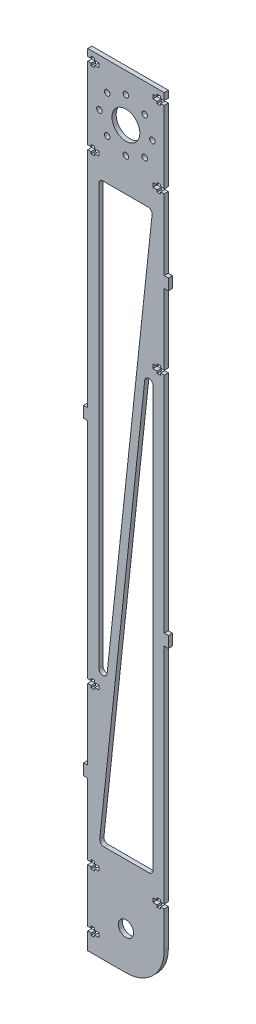
SolidWorks part; units mm, degrees
ref_plane "前视基准面" through (0, 0, 0) normal (0, 0, 1) x (1, 0, 0)
ref_plane "上视基准面" through (0, 0, 0) normal (0, 1, 0) x (1, 0, 0)
ref_plane "右视基准面" through (0, 0, 0) normal (1, 0, 0) x (0, 0, -1)
sketch "草图1" plane through (0, 0, 0) normal (0, 0, 1) x (1, 0, 0)
  line L50 (249.9534, 275.9629) -> (249.9534, 255.9629) construction
  line L71 (269.9534, 275.9629) -> (249.9534, 275.9629) construction
  line L261 (249.9534, 275.9629) -> (249.9534, -224.0371) construction
  line L264 (272.4534, 235.9629) -> (272.4534, -184.0371) construction
  line L265 (272.4534, -184.0371) -> (227.4534, -184.0371) construction
  line L266 (227.4534, -184.0371) -> (227.4534, 235.9629) construction
  line L267 (227.4534, 235.9629) -> (272.4534, 235.9629) construction
  line L268 (272.4534, 235.9629) -> (227.4534, -184.0371) construction
  line L270 (233.4534, 232.9629) -> (265.7762, 232.9629)
  line L271 (268.7591, 229.6433) -> (236.4363, -72.0362)
  line L272 (230.4534, -71.7166) -> (230.4534, 229.9629)
  line L273 (269.4534, 123.6424) -> (269.4534, -178.0371)
  line L274 (266.4534, -181.0371) -> (234.1306, -181.0371)
  line L275 (263.4704, 123.962) -> (231.1476, -177.7175)
  line L276 (269.4534, 179.8027) -> (269.4534, -181.0371) construction
  line L277 (269.4534, -181.0371) -> (230.792, -181.0371) construction
  line L278 (269.4534, 179.8027) -> (230.792, -181.0371) construction
  line L279 (230.4534, -127.8768) -> (230.4534, 232.9629) construction
  line L280 (269.1148, 232.9629) -> (230.4534, -127.8768) construction
  line L281 (230.4534, 232.9629) -> (269.1148, 232.9629) construction
  line L282 (224.9534, -85.2166) -> (224.9534, -86.7166)
  line L283 (224.9534, -82.2166) -> (224.9534, -80.7166)
  line L284 (222.4534, -82.2166) -> (224.9534, -82.2166)
  line L285 (224.9534, -86.7166) -> (227.5534, -86.7166)
  line L286 (227.5534, -86.7166) -> (227.5534, -85.2166)
  line L287 (227.5534, -85.2166) -> (230.5534, -85.2166)
  line L288 (230.5534, -82.2166) -> (230.5534, -85.2166)
  line L289 (227.5534, -82.2166) -> (230.5534, -82.2166)
  line L290 (227.5534, -80.7166) -> (227.5534, -82.2166)
  line L291 (224.9534, -80.7166) -> (227.5534, -80.7166)
  line L292 (224.9534, -85.2166) -> (222.4534, -85.2166)
  line L293 (230.5534, -83.7166) -> (222.4534, -83.7166) construction
  line L294 (233.4534, -71.7166) -> (233.4534, -83.7166) construction
  line L295 (233.4534, -83.7166) -> (222.4534, -83.7166) construction
  line L296 (249.9534, -196.5371) -> (222.4534, -196.5371) construction
  line L297 (249.9534, 248.4629) -> (222.4534, 248.4629) construction
  line L298 (224.9534, -198.0371) -> (224.9534, -199.5371)
  line L299 (224.9534, -195.0371) -> (224.9534, -193.5371)
  line L300 (222.4534, -195.0371) -> (224.9534, -195.0371)
  line L301 (224.9534, -199.5371) -> (227.5534, -199.5371)
  line L302 (227.5534, -199.5371) -> (227.5534, -198.0371)
  line L303 (227.5534, -198.0371) -> (230.5534, -198.0371)
  line L304 (230.5534, -195.0371) -> (230.5534, -198.0371)
  line L305 (227.5534, -195.0371) -> (230.5534, -195.0371)
  line L306 (227.5534, -193.5371) -> (227.5534, -195.0371)
  line L307 (224.9534, -193.5371) -> (227.5534, -193.5371)
  line L308 (224.9534, -198.0371) -> (222.4534, -198.0371)
  line L309 (230.5534, -196.5371) -> (222.4534, -196.5371) construction
  line L310 (224.9534, 246.9629) -> (224.9534, 245.4629)
  line L311 (224.9534, 249.9629) -> (224.9534, 251.4629)
  line L312 (222.4534, 249.9629) -> (224.9534, 249.9629)
  line L313 (224.9534, 245.4629) -> (227.5534, 245.4629)
  line L314 (227.5534, 245.4629) -> (227.5534, 246.9629)
  line L315 (227.5534, 246.9629) -> (230.5534, 246.9629)
  line L316 (230.5534, 249.9629) -> (230.5534, 246.9629)
  line L317 (227.5534, 249.9629) -> (230.5534, 249.9629)
  line L318 (227.5534, 251.4629) -> (227.5534, 249.9629)
  line L319 (224.9534, 251.4629) -> (227.5534, 251.4629)
  line L320 (224.9534, 246.9629) -> (222.4534, 246.9629)
  line L321 (230.5534, 248.4629) -> (222.4534, 248.4629) construction
  line L322 (222.4534, -85.2166) -> (222.4534, -195.0371) construction
  line L323 (222.4534, -198.0371) -> (222.4534, -224.0371)
  line L324 (222.4534, 246.9629) -> (222.4534, -82.2166) construction
  line L325 (222.4534, 275.9629) -> (222.4534, 249.9629)
  line L326 (277.4534, -195.0371) -> (274.9534, -195.0371)
  line L327 (274.9534, -195.0371) -> (274.9534, -193.5371)
  line L328 (274.9534, -193.5371) -> (272.3534, -193.5371)
  line L329 (272.3534, -193.5371) -> (272.3534, -195.0371)
  line L330 (272.3534, -195.0371) -> (269.3534, -195.0371)
  line L331 (269.3534, -195.0371) -> (269.3534, -198.0371)
  line L332 (272.3534, -198.0371) -> (269.3534, -198.0371)
  line L333 (274.9534, -199.5371) -> (272.3534, -199.5371)
  line L334 (272.3534, -199.5371) -> (272.3534, -198.0371)
  line L335 (274.9534, -198.0371) -> (274.9534, -199.5371)
  line L336 (274.9534, -198.0371) -> (277.4534, -198.0371)
  line L337 (272.3534, 249.9629) -> (269.3534, 249.9629)
  line L338 (269.3534, 249.9629) -> (269.3534, 246.9629)
  line L339 (272.3534, 246.9629) -> (269.3534, 246.9629)
  line L340 (272.3534, 245.4629) -> (272.3534, 246.9629)
  line L341 (274.9534, 245.4629) -> (272.3534, 245.4629)
  line L342 (274.9534, 246.9629) -> (274.9534, 245.4629)
  line L343 (274.9534, 246.9629) -> (277.4534, 246.9629)
  line L344 (277.4534, 249.9629) -> (274.9534, 249.9629)
  line L345 (274.9534, 249.9629) -> (274.9534, 251.4629)
  line L346 (274.9534, 251.4629) -> (272.3534, 251.4629)
  line L347 (272.3534, 251.4629) -> (272.3534, 249.9629)
  line L348 (266.4534, 123.6424) -> (266.4534, 135.6424) construction
  line L349 (274.9534, 137.1424) -> (274.9534, 138.6424)
  line L350 (274.9534, 134.1424) -> (274.9534, 132.6424)
  line L351 (277.4534, 134.1424) -> (274.9534, 134.1424)
  line L352 (274.9534, 138.6424) -> (272.3534, 138.6424)
  line L353 (272.3534, 138.6424) -> (272.3534, 137.1424)
  line L354 (272.3534, 137.1424) -> (269.3534, 137.1424)
  line L355 (269.3534, 134.1424) -> (269.3534, 137.1424)
  line L356 (272.3534, 134.1424) -> (269.3534, 134.1424)
  line L357 (272.3534, 132.6424) -> (272.3534, 134.1424)
  line L358 (274.9534, 132.6424) -> (272.3534, 132.6424)
  line L359 (274.9534, 137.1424) -> (277.4534, 137.1424)
  line L360 (269.3534, 135.6424) -> (277.4534, 135.6424) construction
  line L361 (266.4534, 135.6424) -> (277.4534, 135.6424) construction
  line L362 (277.4534, 301.9629) -> (277.4534, 249.9629)
  line L363 (277.4534, 246.9629) -> (277.4534, 137.1424) construction
  line L364 (277.4534, 134.1424) -> (277.4534, -195.0371) construction
  line L365 (277.4534, -198.0371) -> (277.4534, -224.0371)
  line L366 (222.4534, 304.9629) -> (222.4534, 309.9629)
  line L367 (272.3534, 300.4629) -> (272.3534, 301.9629)
  line L368 (274.9534, 300.4629) -> (272.3534, 300.4629)
  line L369 (274.9534, 301.9629) -> (274.9534, 300.4629)
  line L370 (277.4534, 301.9629) -> (274.9534, 301.9629)
  line L371 (274.9534, 304.9629) -> (277.4534, 304.9629)
  line L372 (274.9534, 304.9629) -> (274.9534, 306.4629)
  line L373 (274.9534, 306.4629) -> (272.3534, 306.4629)
  line L374 (272.3534, 306.4629) -> (272.3534, 304.9629)
  line L375 (272.3534, 304.9629) -> (269.3534, 304.9629)
  line L376 (269.3534, 301.9629) -> (269.3534, 304.9629)
  line L377 (272.3534, 301.9629) -> (269.3534, 301.9629)
  line L378 (230.5534, 303.4629) -> (222.4534, 303.4629) construction
  line L379 (224.9534, 304.9629) -> (222.4534, 304.9629)
  line L380 (224.9534, 300.4629) -> (227.5534, 300.4629)
  line L381 (227.5534, 300.4629) -> (227.5534, 301.9629)
  line L382 (227.5534, 301.9629) -> (230.5534, 301.9629)
  line L383 (230.5534, 301.9629) -> (230.5534, 304.9629)
  line L384 (227.5534, 304.9629) -> (230.5534, 304.9629)
  line L385 (227.5534, 306.4629) -> (227.5534, 304.9629)
  line L386 (224.9534, 306.4629) -> (227.5534, 306.4629)
  line L387 (222.4534, 301.9629) -> (224.9534, 301.9629)
  line L388 (224.9534, 301.9629) -> (224.9534, 300.4629)
  line L389 (224.9534, 304.9629) -> (224.9534, 306.4629)
  line L390 (222.4534, 309.9629) -> (277.4534, 309.9629)
  line L391 (277.4534, 309.9629) -> (277.4534, 304.9629)
  line L392 (222.4534, 301.9629) -> (222.4534, 275.9629)
  line L394 (222.4534, -251.5371) -> (249.9534, -251.5371)
  line L395 (230.5534, -237.7871) -> (222.4534, -237.7871) construction
  line L396 (224.9534, -236.2871) -> (222.4534, -236.2871)
  line L397 (224.9534, -240.7871) -> (227.5534, -240.7871)
  line L398 (227.5534, -240.7871) -> (227.5534, -239.2871)
  line L399 (227.5534, -239.2871) -> (230.5534, -239.2871)
  line L400 (230.5534, -239.2871) -> (230.5534, -236.2871)
  line L401 (227.5534, -236.2871) -> (230.5534, -236.2871)
  line L402 (227.5534, -234.7871) -> (227.5534, -236.2871)
  line L403 (224.9534, -234.7871) -> (227.5534, -234.7871)
  line L404 (222.4534, -239.2871) -> (224.9534, -239.2871)
  line L405 (224.9534, -239.2871) -> (224.9534, -240.7871)
  line L406 (224.9534, -236.2871) -> (224.9534, -234.7871)
  line L407 (222.4534, -237.7871) -> (227.5534, -237.7871) construction
  line L408 (222.4534, -236.2871) -> (222.4534, -224.0371)
  line L409 (222.4534, -239.2871) -> (222.4534, -251.5371)
  line L410 (277.4534, 192.0527) -> (280.4534, 192.0527) construction
  line L411 (280.4534, 192.0527) -> (280.4534, 196.0527)
  line L412 (280.4534, 196.0527) -> (277.4534, 196.0527)
  line L413 (280.4534, 192.0527) -> (280.4534, 188.0527)
  line L414 (280.4534, 188.0527) -> (277.4534, 188.0527)
  line L415 (277.4534, 188.0527) -> (277.4534, 137.1424)
  line L416 (277.4534, 246.9629) -> (277.4534, 196.0527)
  line L417 (277.4534, -30.4473) -> (280.4534, -30.4473) construction
  line L418 (280.4534, -30.4473) -> (280.4534, -26.4473)
  line L419 (280.4534, -26.4473) -> (277.4534, -26.4473)
  line L420 (280.4534, -30.4473) -> (280.4534, -34.4473)
  line L421 (280.4534, -34.4473) -> (277.4534, -34.4473)
  line L422 (277.4534, -26.4473) -> (277.4534, 134.1424)
  line L423 (277.4534, -34.4473) -> (277.4534, -195.0371)
  line L424 (219.4534, 82.3732) -> (219.4534, 86.3732)
  line L425 (219.4534, 82.3732) -> (219.4534, 78.3732)
  line L426 (219.4534, 78.3732) -> (222.4534, 78.3732)
  line L427 (222.4534, 78.3732) -> (222.4534, -82.2166)
  line L428 (219.4534, 86.3732) -> (222.4534, 86.3732)
  line L429 (222.4534, 86.3732) -> (222.4534, 246.9629)
  line L431 (219.4534, -140.1268) -> (219.4534, -144.1268)
  line L432 (219.4534, -140.1268) -> (219.4534, -136.1268)
  line L433 (219.4534, -136.1268) -> (222.4534, -136.1268)
  line L434 (219.4534, -144.1268) -> (222.4534, -144.1268)
  line L435 (222.4534, -144.1268) -> (222.4534, -195.0371)
  line L436 (222.4534, -85.2166) -> (222.4534, -136.1268)
  circle A14 centre (249.9534, 275.9629) radius 10
  circle A15 centre (249.9534, 275.9629) radius 19 construction
  circle A16 centre (230.9534, 275.9629) radius 2
  circle A17 centre (236.5183, 289.398) radius 2
  circle A18 centre (249.9534, 294.9629) radius 2
  circle A19 centre (263.3884, 289.398) radius 2
  circle A20 centre (268.9534, 275.9629) radius 2
  circle A21 centre (263.3884, 262.5279) radius 2
  circle A22 centre (249.9534, 256.9629) radius 2
  circle A23 centre (236.5183, 262.5279) radius 2
  arc A26 (277.4534, 275.9629) -> (222.4534, 275.9629) centre (249.9534, 275.9629) ccw construction
  arc A27 (277.4534, -224.0371) -> (222.4534, -224.0371) centre (249.9534, -224.0371) cw construction
  circle A28 centre (249.9534, -224.0371) radius 5.5
  arc A29 (269.4534, -178.0371) -> (266.4534, -181.0371) centre (266.4534, -178.0371) cw
  arc A30 (234.1306, -181.0371) -> (231.1476, -177.7175) centre (234.1306, -178.0371) cw
  arc A31 (269.4534, 123.6424) -> (263.4704, 123.962) centre (266.4534, 123.6424) ccw
  arc A32 (230.4534, -71.7166) -> (236.4363, -72.0362) centre (233.4534, -71.7166) ccw
  arc A33 (230.4534, 229.9629) -> (233.4534, 232.9629) centre (233.4534, 229.9629) cw
  arc A34 (268.7591, 229.6433) -> (265.7762, 232.9629) centre (265.7762, 229.9629) ccw
  arc A35 (249.9534, -251.5371) -> (277.4534, -224.0371) centre (249.9534, -224.0371) ccw
  dimension "D1" = 8
  dimension "D5" = 40
  dimension "D6" = 40
  dimension "D7" = 3
  dimension "D2" = 20
extrude "凸台-拉伸1" add sketch "草图1" along normal blind 3
sketch "草图2" plane through (277.4534, 0, 0) normal (1, 0, 0) x (0, 0, -1)
  line L0 (-1.5, 249.9629) -> (-1.5, 246.9629) construction
  line L1 (-3, 249.9629) -> (0, 249.9629) construction
  line L2 (-3, 246.9629) -> (0, 246.9629) construction
  circle A0 centre (-1.5, 248.4629) radius 1.5
sketch "草图3" plane through (222.4534, 0, 0) normal (-1, 0, 0) x (0, 0, 1)
  line L0 (1.5, -198.0371) -> (1.5, -195.0371)
  line L1 (3, -198.0371) -> (0, -198.0371) construction
  line L2 (3, -195.0371) -> (0, -195.0371) construction
  circle A0 centre (1.5, -196.5371) radius 1.5
